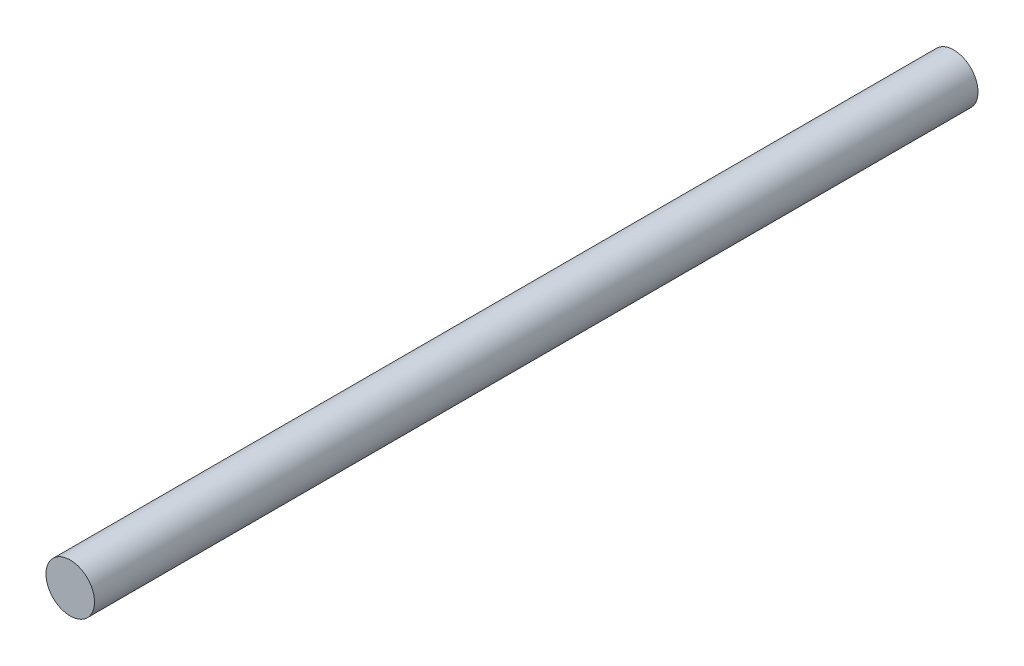
SolidWorks part; units mm, degrees
ref_plane "Front Plane" through (0, 0, 0) normal (0, 0, 1) x (1, 0, 0)
ref_plane "Top Plane" through (0, 0, 0) normal (0, 1, 0) x (1, 0, 0)
ref_plane "Right Plane" through (0, 0, 0) normal (1, 0, 0) x (0, 0, -1)
sketch "Sketch1" plane through (0, 0, 0) normal (0, 0, 1) x (1, 0, 0)
  circle A0 centre (0, 0) radius 5
  dimension "D1" = 10
extrude "Boss-Extrude1" add sketch "Sketch1" along normal blind 182
